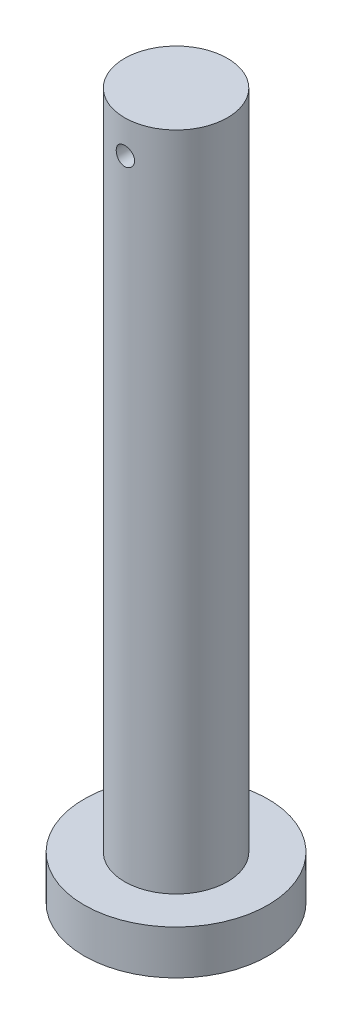
SolidWorks part; units mm, degrees
ref_plane "Front Plane" through (0, 0, 0) normal (0, 0, 1) x (1, 0, 0)
ref_plane "Top Plane" through (0, 0, 0) normal (0, 1, 0) x (1, 0, 0)
ref_plane "Right Plane" through (0, 0, 0) normal (1, 0, 0) x (0, 0, -1)
sketch "Sketch1" plane through (0, 0, 0) normal (0, 1, 0) x (1, 0, 0)
  circle A0 centre (0, 0) radius 25
  dimension "D1" = 50
extrude "Boss-Extrude1" add sketch "Sketch1" along normal blind 12
sketch "Sketch2" plane through (0, 12, 0) normal (0, 1, 0) x (1, 0, 0)
  circle A0 centre (0, 0) radius 14
  dimension "D1" = 28
extrude "Boss-Extrude2" add sketch "Sketch2" along normal blind 180
sketch "Sketch3" plane through (0, 0, 0) normal (0, 0, 1) x (1, 0, 0)
  line L0 (14, 192) -> (-14, 192) construction
  circle A0 centre (0, 183) radius 2.5
  dimension "D1" = 5
  dimension "D2" = 9
extrude "Cut-Extrude1" cut sketch "Sketch3" against normal mid plane 180
